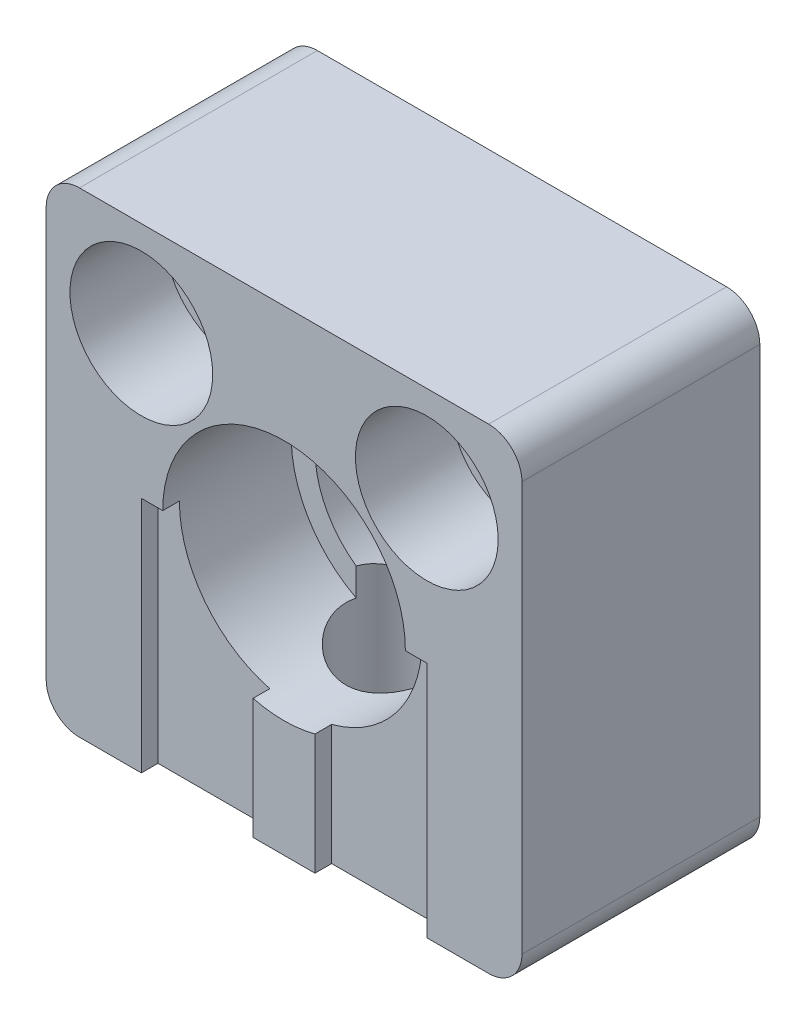
SolidWorks part; units mm, degrees
ref_plane "Front Plane" through (0, 0, 0) normal (0, 0, 1) x (1, 0, 0)
ref_plane "Top Plane" through (0, 0, 0) normal (0, 1, 0) x (1, 0, 0)
ref_plane "Right Plane" through (0, 0, 0) normal (1, 0, 0) x (0, 0, -1)
sketch "Sketch1" plane through (0, 0, 0) normal (0, 1, 0) x (1, 0, 0)
  line L1 (0, 0) -> (10, 0)
  line L2 (0, 0) -> (0, 5)
  line L3 (0, 5) -> (10, 5)
  line L4 (10, 0) -> (10, 5)
  dimension "D1" = 5
  dimension "D2" = 10
extrude "Boss-Extrude1" add sketch "Sketch1" along normal blind 10
sketch "Sketch2" plane through (0, 0, 0) normal (0, 0, 1) x (1, 0, 0)
  line L0 (5, 10) -> (5, 0) construction
  line L1 (0, 10) -> (10, 10) construction
  line L2 (0, 0) -> (10, 0) construction
  line L3 (0, 5) -> (10, 5) construction
  line L4 (0, 10) -> (0, 0) construction
  line L5 (10, 10) -> (10, 0) construction
  circle A0 centre (5, 5) radius 2.05
  dimension "D1" = 4.1
extrude "Cut-Extrude1" cut sketch "Sketch2" against normal through all
sketch "Sketch3" plane through (0, 0, 0) normal (0, 0, 1) x (1, 0, 0)
  line L0 (0, 5) -> (10, 5) construction
  line L1 (0, 10) -> (0, 0) construction
  line L2 (10, 10) -> (10, 0) construction
  line L3 (5, 10) -> (5, 0) construction
  line L4 (0, 10) -> (10, 10) construction
  line L5 (0, 0) -> (10, 0) construction
  circle A0 centre (5, 5) radius 2.55
  dimension "D1" = 5.1
extrude "Cut-Extrude2" cut sketch "Sketch3" against normal blind 2.7
sketch "Sketch5" plane through (0, 0, 0) normal (0, -1, 0) x (1, 0, 0)
  line L0 (0, 0) -> (10, 0) construction
  line L1 (2, 0) -> (4.35, 0)
  line L2 (2, 0) -> (2, -0.35)
  line L3 (2, -0.35) -> (4.35, -0.35)
  line L4 (4.35, 0) -> (4.35, -0.35)
  line L5 (0, -5) -> (0, 0) construction
  line L6 (5.65, 0) -> (8, 0)
  line L7 (5.65, 0) -> (5.65, -0.35)
  line L8 (5.65, -0.35) -> (8, -0.35)
  line L9 (8, 0) -> (8, -0.35)
  line L10 (10, 0) -> (10, -5) construction
  dimension "D1" = 2
  dimension "D2" = 2
  dimension "D3" = 1.3
  dimension "D4" = 2.35
  dimension "D5" = 0.35
  dimension "D6" = 0.35
extrude "Cut-Extrude3" cut sketch "Sketch5" against normal blind 5
sketch "Sketch6" plane through (0, 0, 0) normal (0, 0, 1) x (1, 0, 0)
  line L0 (0, 10) -> (10, 10) construction
  line L1 (0, 10) -> (0, 0) construction
  line L2 (10, 10) -> (10, 0) construction
  circle A0 centre (2, 8) radius 1.5
  circle A1 centre (8, 8) radius 1.5
  dimension "D1" = 3
  dimension "D4" = 3
  dimension "D2" = 2
  dimension "D3" = 2
  dimension "D5" = 2
  dimension "D6" = 2
extrude "Cut-Extrude4" cut sketch "Sketch6" against normal blind 2
sketch "Sketch8" plane through (0, 0, 0) normal (0, -1, 0) x (1, 0, 0)
  line L0 (0, -2.5) -> (10, -2.5) construction
  line L1 (0, -5) -> (0, 0) construction
  line L2 (10, 0) -> (10, -5) construction
  circle A0 centre (5, -2.5) radius 1.2
  dimension "D1" = 2.4
extrude "Cut-Extrude5" cut sketch "Sketch8" against normal blind 3.5
fillet "Fillet1" radius 0.7 4 edges at (0, 10, -2.5) (0, 0, -2.5) (10, 0, -2.5) (10, 10, -2.5)
